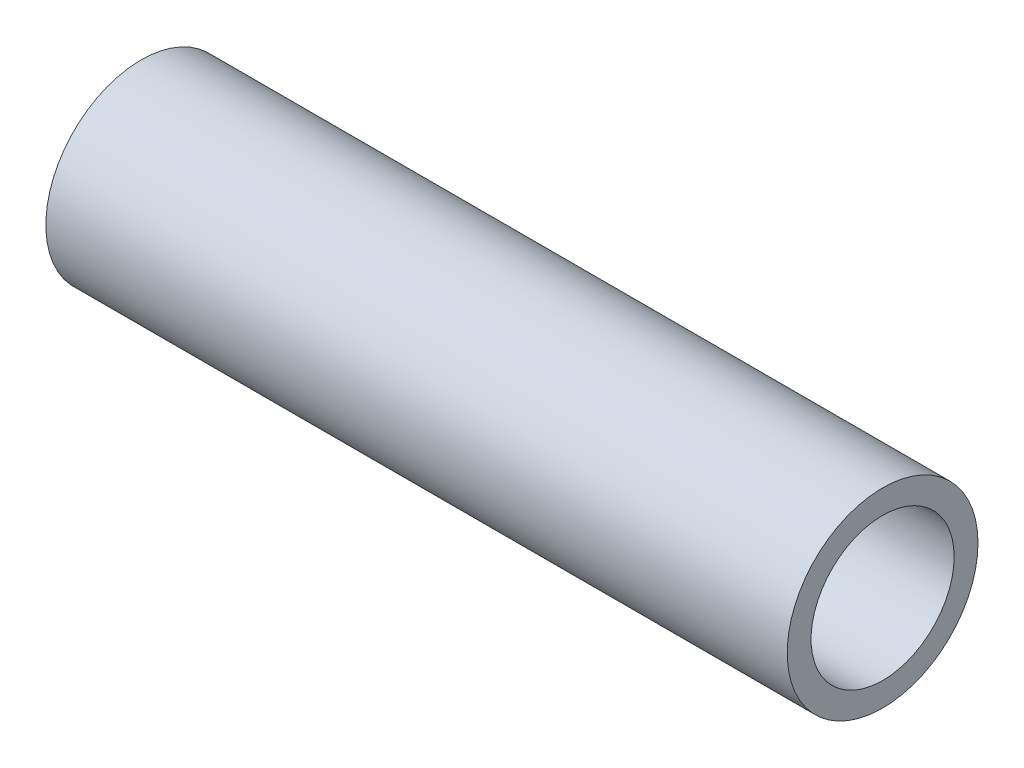
SolidWorks part; units mm, degrees
material "AISI 1020"
ref_plane "Front Plane" through (0, 0, 0) normal (0, 0, 1) x (1, 0, 0)
ref_plane "Top Plane" through (0, 0, 0) normal (0, 1, 0) x (1, 0, 0)
ref_plane "Right Plane" through (0, 0, 0) normal (1, 0, 0) x (0, 0, -1)
sketch "Sketch1" plane through (0, 0, 0) normal (1, 0, 0) x (0, 0, -1)
  circle A0 centre (0, 0) radius 7
  circle A1 centre (0, 0) radius 5.25
  dimension "D1" = 14
  dimension "D2" = 1.75
extrude "Boss-Extrude1" add sketch "Sketch1" along normal blind 54.4
